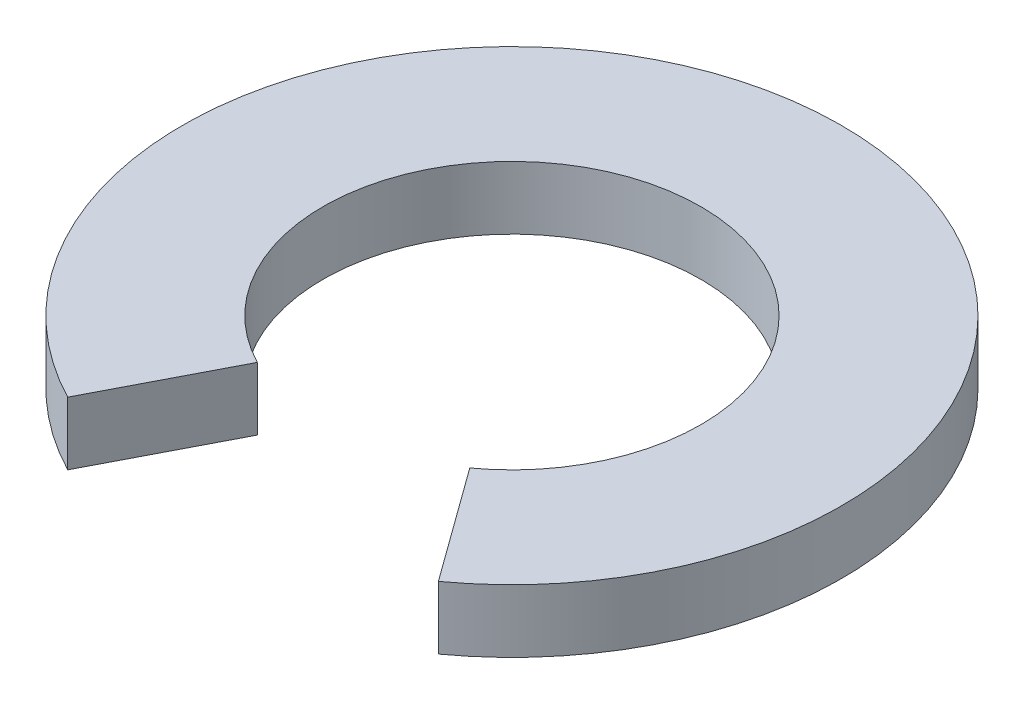
SolidWorks part; units mm, degrees
ref_plane "Front Plane" through (0, 0, 0) normal (0, 0, 1) x (1, 0, 0)
ref_plane "Top Plane" through (0, 0, 0) normal (0, 1, 0) x (1, 0, 0)
ref_plane "Right Plane" through (0, 0, 0) normal (1, 0, 0) x (0, 0, -1)
sketch "Sketch1" plane through (0, 0, 0) normal (0, 1, 0) x (1, 0, 0)
  line L0 (-1.2031, -2.3236) -> (-0.6897, -1.332)
  line L1 (1.5351, -2.119) -> (0.88, -1.2147)
  line L2 (-1.7346, 1.9591) -> (-0.9943, 1.1231)
  line L3 (1.7346, 1.9591) -> (0.9424, 1.167)
  circle A0 centre (0, 0) radius 2.6166
  circle A1 centre (0, 0) radius 1.5
  dimension "D1" = 3
extrude "Boss-Extrude1" add sketch "Sketch1" along normal blind 0.5 contours A1 L3 A0 L2 | A1 L2 A0 L0 | A1 L1 A0 L3
